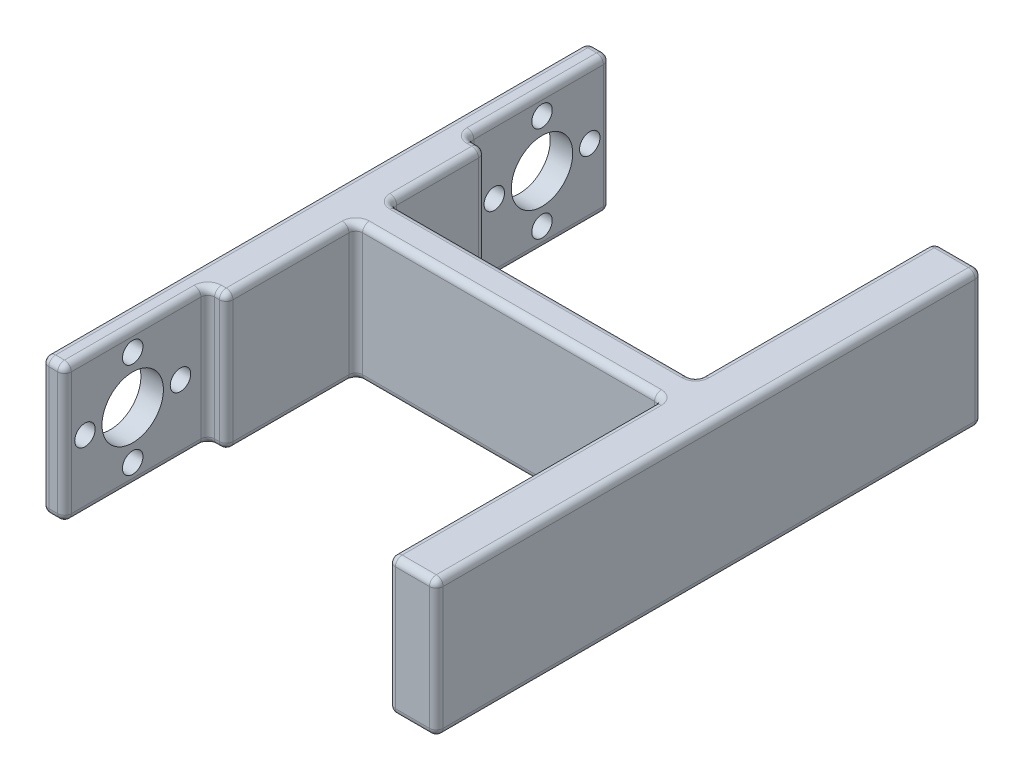
SolidWorks part; units mm, degrees
material "ABS"
ref_plane "Front Plane" through (0, 0, 0) normal (0, 0, 1) x (1, 0, 0)
ref_plane "Top Plane" through (0, 0, 0) normal (0, 1, 0) x (1, 0, 0)
ref_plane "Right Plane" through (0, 0, 0) normal (1, 0, 0) x (0, 0, -1)
sketch "Sketch2" plane through (0, 0, 0) normal (0, 1, 0) x (1, 0, 0)
  line L0 (0, 0) -> (0, -80)
  line L1 (0, -80) -> (6, -80)
  line L2 (6, -80) -> (6, -40)
  line L3 (6, -40) -> (50.8, -40)
  line L4 (50.8, -40) -> (50.8, -80)
  line L5 (50.8, -80) -> (57.8, -80)
  line L6 (57.8, -80) -> (57.8, 0)
  line L7 (57.8, 0) -> (50.8, 0)
  line L8 (50.8, 0) -> (50.8, -35)
  line L9 (50.8, -35) -> (6, -35)
  line L10 (6, -35) -> (6, 0)
  line L11 (6, 0) -> (0, 0)
  dimension "D1" = 80
  dimension "D2" = 6
  dimension "D3" = 40
  dimension "D4" = 44.8
  dimension "D5" = 7
  dimension "D6" = 80
  dimension "D7" = 44.8
extrude "Boss-Extrude1" add sketch "Sketch2" along normal blind 20
sketch "Sketch3" plane through (50.8, 0, 0) normal (-1, 0, 0) x (0, 0, 1)
  line L0 (0, 20) -> (80, 20) construction
  line L1 (80, 20) -> (80, 0) construction
  line L2 (40, 20) -> (40, 0) construction
  circle A0 centre (70, 10) radius 8.1
  circle A1 centre (10, 10) radius 8.1
  dimension "D1" = 16.2
  dimension "D2" = 10
  dimension "D3" = 10
sketch "Sketch4" plane through (0, 0, 0) normal (-1, 0, 0) x (0, 0, 1)
  line L3 (0, 20) -> (80, 20) construction
  line L4 (80, 20) -> (80, 0) construction
  circle A3 centre (70, 10) radius 7 construction
  circle A4 centre (70, 17) radius 1.5
  circle A5 centre (77, 10) radius 1.5
  circle A6 centre (70, 3) radius 1.5
  circle A7 centre (63, 10) radius 1.5
  circle A8 centre (70, 10) radius 4.5
  dimension "D1" = 14
  dimension "D2" = 10
  dimension "D3" = 10
  dimension "D4" = 3
  dimension "D5" = 3
  dimension "D6" = 3
  dimension "D7" = 3
  dimension "D8" = 9
extrude "Cut-Extrude1" cut sketch "Sketch4" against normal blind 10
sketch "Sketch5" plane through (0, 0, 0) normal (-1, 0, 0) x (0, 0, 1)
  line L0 (0, 0) -> (80, 0) construction
  line L1 (59, 0) -> (80, 0)
  line L2 (59, 0) -> (59, 20)
  line L3 (59, 20) -> (80, 20)
  line L4 (80, 0) -> (80, 20)
  dimension "D1" = 21
extrude "Cut-Extrude2" cut sketch "Sketch5" against normal blind 2.7 from offset 3.3 offset against normal yes
ref_plane "Plane1" through (0, 0, 40) normal (0, 0, 1) x (1, 0, 0)
mirror "Mirror1" about plane through (0, 0, 40) normal (0, 0, 1) of "Cut-Extrude1", "Cut-Extrude2"
fillet "Fillet1" radius 1 48 edges at (1.65, 0, 80) (6, 0, 49.5) (28.4, 0, 40) (50.8, 0, 60) (54.3, 0, 80) (57.8, 0, 40) (54.3, 0, 0) (50.8, 0, 17.5) (28.4, 0, 35) (6, 0, 28) (1.65, 0, 0) (0, 0, 40) (4.65, 0, 59) (4.65, 20, 59) (0, 20, 40) (1.65, 20, 0) (6, 20, 28) (28.4, 20, 35) (50.8, 20, 17.5) (54.3, 20, 0) (57.8, 20, 40) (54.3, 20, 80) (50.8, 20, 60) (28.4, 20, 40) (6, 20, 49.5) (1.65, 20, 80) (57.8, 10, 0) (50.8, 10, 0) (0, 10, 0) (50.8, 10, 35) (6, 10, 35) (6, 10, 40) (50.8, 10, 40) (50.8, 10, 80) (57.8, 10, 80) (4.65, 0, 21) (4.65, 20, 21) (3.3, 0, 69.5) (3.3, 0, 10.5) (3.3, 20, 69.5) (3.3, 20, 10.5) (6, 10, 59) (3.3, 10, 59) (3.3, 10, 80) (0, 10, 80) (3.3, 10, 0) (3.3, 10, 21) (6, 10, 21)
extrude "Cut-Extrude3" cut sketch "Sketch3" against normal blind 5
